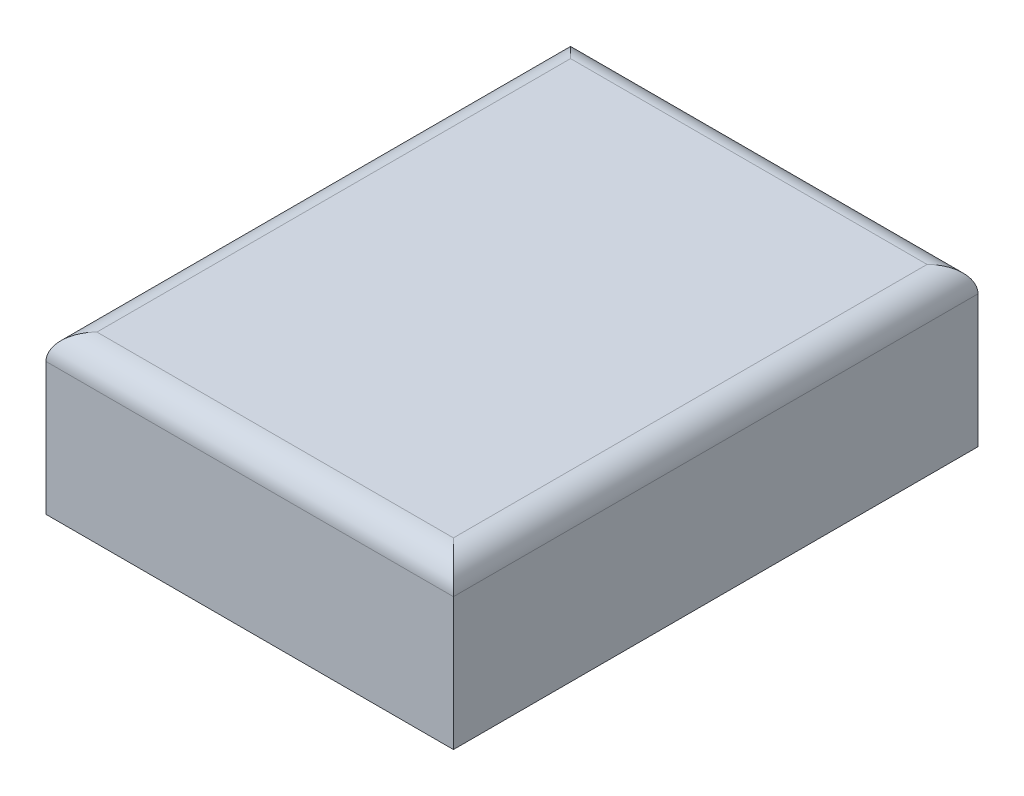
SolidWorks part; units mm, degrees
material "Epoxy, Unfilled"
ref_plane "Front Plane" through (0, 0, 0) normal (0, 0, 1) x (1, 0, 0)
ref_plane "Top Plane" through (0, 0, 0) normal (0, 1, 0) x (1, 0, 0)
ref_plane "Right Plane" through (0, 0, 0) normal (1, 0, 0) x (0, 0, -1)
sketch "Sketch1" plane through (0, 0, 0) normal (0, 1, 0) x (1, 0, 0)
  line L1 (-0.8, 1.03) -> (0.8, 1.03)
  line L2 (-0.8, 1.03) -> (-0.8, -1.03)
  line L3 (-0.8, -1.03) -> (0.8, -1.03)
  line L4 (0.8, 1.03) -> (0.8, -1.03)
  line L5 (-0.8, 1.03) -> (0.8, -1.03) construction
  line L6 (-0.8, -1.03) -> (0.8, 1.03) construction
  point P0 (0, 0)
  dimension "D1" = 2.06
  dimension "D2" = 1.6
extrude "Boss-Extrude1" add sketch "Sketch1" along normal blind 0.62
fillet "Fillet1" radius 0.1 4 edges at (-0.8, 0.62, 0) (0.8, 0.62, 0) (0, 0.62, -1.03) (0, 0.62, 1.03)
